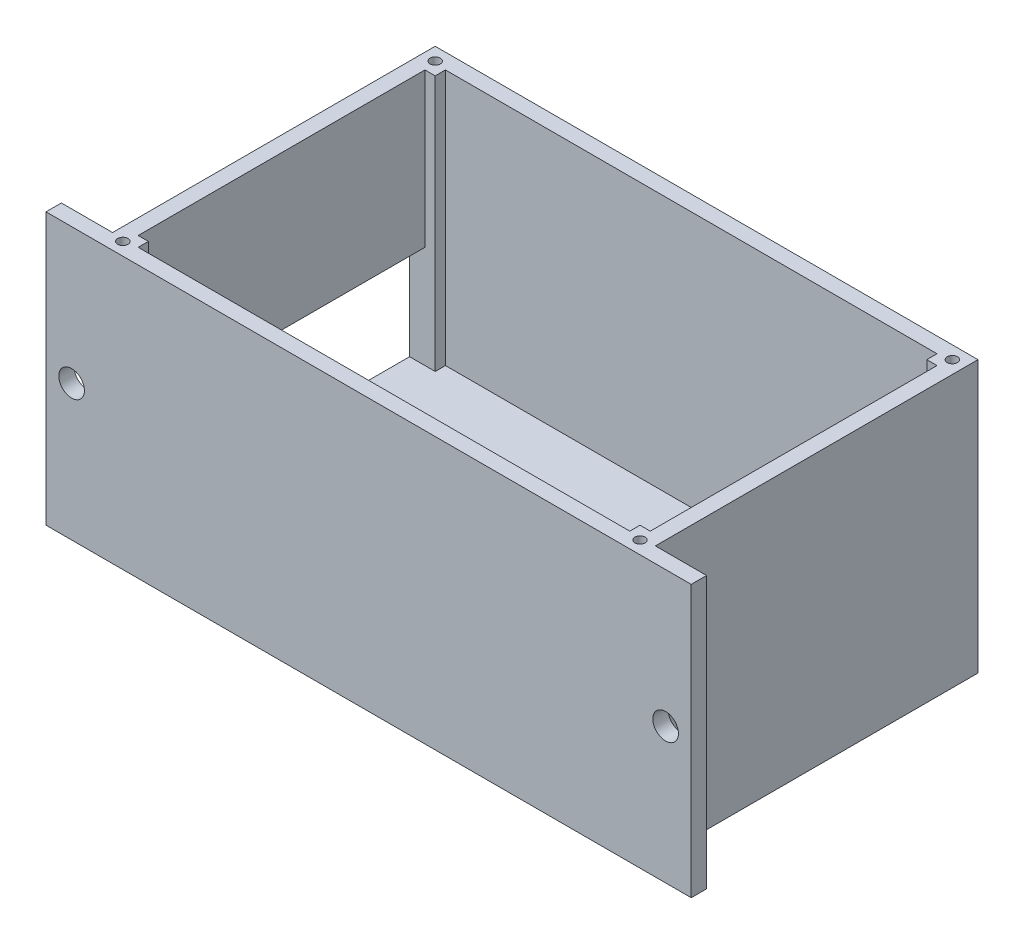
SolidWorks part; units mm, degrees
ref_plane "Alzado" through (0, 0, 0) normal (0, 0, 1) x (1, 0, 0)
ref_plane "Planta" through (0, 0, 0) normal (0, 1, 0) x (1, 0, 0)
ref_plane "Vista lateral" through (0, 0, 0) normal (1, 0, 0) x (0, 0, -1)
sketch "Croquis1" plane through (0, 0, 0) normal (0, 1, 0) x (1, 0, 0)
  line L1 (-45.3287, 38.9273) -> (54.6713, 38.9273)
  line L2 (-45.3287, 38.9273) -> (-45.3287, -21.0727)
  line L3 (-45.3287, -21.0727) -> (54.6713, -21.0727)
  line L4 (54.6713, 38.9273) -> (54.6713, -21.0727)
  dimension "D1" = 100
  dimension "D2" = 60
extrude "Saliente-Extruir1" add sketch "Croquis1" along normal blind 3
sketch "Croquis2" plane through (0, 3, 0) normal (0, 1, 0) x (1, 0, 0)
  line L1 (-45.3287, 38.9273) -> (54.6713, 38.9273)
  line L2 (-45.3287, 38.9273) -> (-45.3287, -21.0727)
  line L3 (-45.3287, -21.0727) -> (54.6713, -21.0727)
  line L4 (54.6713, 38.9273) -> (54.6713, -21.0727)
  line L5 (-48.3287, 41.9273) -> (57.6713, 41.9273)
  line L6 (-48.3287, 41.9273) -> (-48.3287, -24.0727)
  line L7 (-48.3287, -24.0727) -> (57.6713, -24.0727)
  line L8 (57.6713, 41.9273) -> (57.6713, -24.0727)
  dimension "D1" = 3
  dimension "D2" = 3
  dimension "D3" = 3
  dimension "D4" = 3
extrude "Saliente-Extruir2" add sketch "Croquis2" along normal blind 50 and the other way blind 3
sketch "Croquis3" plane through (0, 3, 0) normal (0, 1, 0) x (1, 0, 0)
  line L0 (-45.3287, 38.9273) -> (-45.3287, -21.0727) construction
  line L1 (-45.3287, 36.9273) -> (-43.3287, 36.9273)
  line L2 (-45.3287, 36.9273) -> (-45.3287, 38.9273)
  line L3 (-45.3287, 38.9273) -> (-43.3287, 38.9273)
  line L4 (-43.3287, 36.9273) -> (-43.3287, 38.9273)
  line L5 (54.6713, 38.9273) -> (-45.3287, 38.9273) construction
  line L6 (-45.3287, -21.0727) -> (54.6713, -21.0727) construction
  line L7 (-43.3287, -21.0727) -> (-45.3287, -21.0727)
  line L8 (-43.3287, -21.0727) -> (-43.3287, -19.0727)
  line L9 (-43.3287, -19.0727) -> (-45.3287, -19.0727)
  line L10 (-45.3287, -21.0727) -> (-45.3287, -19.0727)
  line L11 (-45.3287, 38.9273) -> (-45.3287, -21.0727) construction
  line L12 (54.6713, -21.0727) -> (54.6713, 38.9273) construction
  line L13 (54.6713, -19.0727) -> (52.6713, -19.0727)
  line L14 (54.6713, -19.0727) -> (54.6713, -21.0727)
  line L15 (54.6713, -21.0727) -> (52.6713, -21.0727)
  line L16 (52.6713, -19.0727) -> (52.6713, -21.0727)
  line L17 (54.6713, 38.9273) -> (-45.3287, 38.9273) construction
  line L18 (54.6713, 36.9273) -> (52.6713, 36.9273)
  line L19 (54.6713, 36.9273) -> (54.6713, 38.9273)
  line L20 (54.6713, 38.9273) -> (52.6713, 38.9273)
  line L21 (52.6713, 36.9273) -> (52.6713, 38.9273)
  dimension "D1" = 2
  dimension "D2" = 2
  dimension "D3" = 2
  dimension "D4" = 2
  dimension "D5" = 2
  dimension "D6" = 2
extrude "Saliente-Extruir3" add sketch "Croquis3" along normal blind 50
sketch "Croquis4" plane through (-48.3287, 0, 0) normal (-1, 0, 0) x (0, 0, 1)
  line L0 (-41.9273, 0) -> (-41.9273, 53) construction
  line L1 (-36.9273, 3) -> (-6.9273, 3)
  line L2 (-36.9273, 3) -> (-36.9273, 23)
  line L3 (-36.9273, 23) -> (-6.9273, 23)
  line L4 (-6.9273, 3) -> (-6.9273, 23)
  line L5 (-41.9273, 0) -> (24.0727, 0) construction
  line L6 (24.0727, 0) -> (24.0727, 53) construction
  line L7 (19.0727, 3) -> (9.0727, 3)
  line L8 (19.0727, 3) -> (19.0727, 13)
  line L9 (19.0727, 13) -> (9.0727, 13)
  line L10 (9.0727, 3) -> (9.0727, 13)
  dimension "D1" = 5
  dimension "D2" = 3
  dimension "D3" = 20
  dimension "D4" = 30
  dimension "D5" = 5
  dimension "D6" = 10
  dimension "D7" = 10
extrude "Cortar-Extruir2" cut sketch "Croquis4" against normal blind 24
sketch "Croquis5" plane through (0, 0, -41.9273) normal (0, 0, -1) x (-1, 0, 0)
  line L0 (-57.6713, 0) -> (48.3287, 0) construction
  line L1 (28.3287, 5) -> (2.3287, 5)
  line L2 (28.3287, 5) -> (28.3287, 31)
  line L3 (28.3287, 31) -> (2.3287, 31)
  line L4 (2.3287, 5) -> (2.3287, 31)
  line L5 (48.3287, 0) -> (48.3287, 53) construction
  line L7 (30.3287, 3) -> (0.3287, 3)
  line L8 (30.3287, 3) -> (30.3287, 33)
  line L9 (30.3287, 33) -> (0.3287, 33)
  line L10 (0.3287, 3) -> (0.3287, 33)
  dimension "D1" = 5
  dimension "D2" = 20
  dimension "D3" = 26
  dimension "D4" = 26
  dimension "D5" = 2
  dimension "D6" = 2
  dimension "D7" = 2
  dimension "D8" = 2
extrude "Saliente-Extruir4" add sketch "Croquis5" along normal blind 6
sketch "Croquis6" plane through (0, 0, -47.9273) normal (0, 0, -1) x (-1, 0, 0)
  line L1 (28.3287, 5) -> (28.3287, 31) construction
  line L2 (28.3287, 19) -> (30.3287, 19)
  line L3 (28.3287, 19) -> (28.3287, 17)
  line L4 (28.3287, 17) -> (30.3287, 17)
  line L5 (30.3287, 19) -> (30.3287, 17)
  line L6 (30.3287, 3) -> (30.3287, 33) construction
  line L7 (30.3287, 33) -> (0.3287, 33) construction
  line L8 (0.3287, 3) -> (30.3287, 3) construction
  dimension "D1" = 14
  dimension "D2" = 14
extrude "Cortar-Extruir3" cut sketch "Croquis6" against normal blind 6
sketch "Croquis7" plane through (0, 0, -41.9273) normal (0, 0, -1) x (-1, 0, 0)
  line L0 (-57.6713, 0) -> (-57.6713, 53) construction
  line L1 (-52.6713, 18) -> (-37.6713, 18)
  line L2 (-52.6713, 18) -> (-52.6713, 3)
  line L3 (-52.6713, 3) -> (-37.6713, 3)
  line L4 (-37.6713, 18) -> (-37.6713, 3)
  line L5 (-57.6713, 0) -> (48.3287, 0) construction
  dimension "D1" = 5
  dimension "D2" = 3
  dimension "D3" = 15
  dimension "D4" = 15
extrude "Cortar-Extruir4" cut sketch "Croquis7" against normal blind 6
sketch "Croquis8" plane through (0, 53, 0) normal (0, 1, 0) x (1, 0, 0)
  line L0 (57.6713, 41.9273) -> (-48.3287, 41.9273) construction
  line L1 (-48.3287, 41.9273) -> (-48.3287, -24.0727) construction
  line L2 (57.6713, -24.0727) -> (57.6713, 41.9273) construction
  line L3 (-48.3287, -24.0727) -> (57.6713, -24.0727) construction
  circle A0 centre (-45.8287, 39.4273) radius 1
  circle A1 centre (55.1713, 39.4273) radius 1
  circle A2 centre (55.1713, -21.5727) radius 1
  circle A3 centre (-45.8287, -21.5727) radius 1
  dimension "D1" = 2.5
  dimension "D3" = 2.5
  dimension "D4" = 2.5
  dimension "D2" = 2.5
extrude "Cortar-Extruir5" cut sketch "Croquis8" against normal blind 53
sketch "Croquis9" plane through (57.6713, 0, 0) normal (1, 0, 0) x (0, 0, -1)
  line L0 (-24.0727, 0) -> (41.9273, 0) construction
  line L1 (-24.0727, 53) -> (-21.0727, 53)
  line L2 (-24.0727, 53) -> (-24.0727, 0)
  line L3 (-24.0727, 0) -> (-21.0727, 0)
  line L4 (-21.0727, 53) -> (-21.0727, 0)
  dimension "D1" = 3
  dimension "D2" = 0
extrude "Saliente-Extruir5" add sketch "Croquis9" along normal blind 10
sketch "Croquis10" plane through (-48.3287, 0, 0) normal (-1, 0, 0) x (0, 0, 1)
  line L0 (-41.9273, 53) -> (24.0727, 53) construction
  line L1 (24.0727, 0) -> (21.0727, 0)
  line L2 (24.0727, 0) -> (24.0727, 53)
  line L3 (24.0727, 53) -> (21.0727, 53)
  line L4 (21.0727, 0) -> (21.0727, 53)
  dimension "D1" = 3
  dimension "D2" = 0
extrude "Saliente-Extruir6" add sketch "Croquis10" along normal blind 10
sketch "Croquis12" plane through (0, 0, 21.0727) normal (0, 0, -1) x (-1, 0, 0)
  line L0 (-67.6713, 53) -> (-57.6713, 53) construction
  line L1 (-67.6713, 0) -> (-67.6713, 53) construction
  line L2 (58.3287, 53) -> (58.3287, 0) construction
  circle A0 centre (-62.6713, 26.5) radius 2.5
  circle A1 centre (53.3287, 26.5) radius 2.5
  dimension "D1" = 26.5
  dimension "D3" = 5
  dimension "D2" = 5
extrude "Cortar-Extruir6" cut sketch "Croquis12" against normal blind 10
